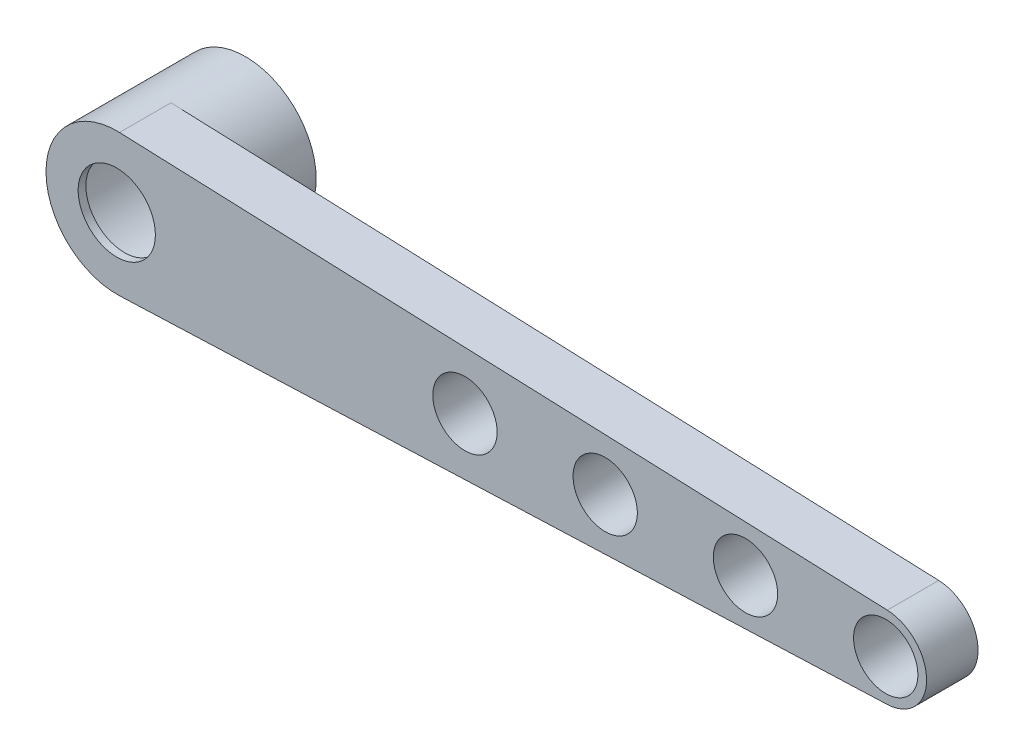
SolidWorks part; units mm, degrees
ref_plane "前视基准面" through (0, 0, 0) normal (0, 0, 1) x (1, 0, 0)
ref_plane "上视基准面" through (0, 0, 0) normal (0, 1, 0) x (1, 0, 0)
ref_plane "右视基准面" through (0, 0, 0) normal (1, 0, 0) x (0, 0, -1)
sketch "草图1" plane through (0, 0, 0) normal (0, 0, 1) x (1, 0, 0)
  circle A0 centre (0, 0) radius 2.75
  dimension "D1" = 5.5
extrude "凸台-拉伸1" add sketch "草图1" along normal blind 5
sketch "草图2" plane through (0, 0, 0) normal (0, 0, -1) x (-1, 0, 0)
  circle A0 centre (0, 0) radius 2.5
  dimension "D1" = 5
extrude "切除-拉伸1" cut sketch "草图2" against normal blind 4.7
sketch "草图3" plane through (0, 0, 5) normal (0, 0, 1) x (1, 0, 0)
  circle A0 centre (0, 0) radius 1.5
  dimension "D1" = 3
extrude "切除-拉伸2" cut sketch "草图3" against normal blind 4.7
sketch "草图4" plane through (0, 0, 5) normal (0, 0, 1) x (1, 0, 0)
  line L0 (0.1066, 2.7479) -> (29.9416, 1.591)
  line L1 (0.1072, -2.7479) -> (29.9419, -1.5841)
  line L2 (16.1859, 13.4331) -> (20.7698, 13.4331)
  line L3 (0.4204, 13.4331) -> (0.4204, 19.2708)
  line L4 (0.4204, 13.4331) -> (16.1859, 13.4331)
  line L5 (0.4204, 19.2708) -> (14.7998, 19.2708)
  line L6 (17.1579, 16.352) -> (1.1299, 16.352) construction
  line L7 (8.3031, 13.4331) -> (8.3031, 19.4331) construction
  line L8 (20.7698, 13.4331) -> (20.7698, 19.2708)
  line L9 (20.7698, 19.2708) -> (14.7998, 19.2708)
  arc A0 (29.9416, 1.591) -> (29.9419, -1.5841) centre (29.88, 0.0035) cw
  circle A2 centre (24.43, 0) radius 1.25
  circle A3 centre (29.88, 0.0035) radius 1.25
  circle A4 centre (0, 0) radius 2.75 construction
  circle A5 centre (2.4204, 16.352) radius 1.25
  circle A6 centre (7.8704, 16.352) radius 1.25
  circle A7 centre (13.3204, 16.352) radius 1.25
  circle A8 centre (18.7698, 16.4323) radius 1.25
  circle A9 centre (18.98, 0) radius 1.25
  circle A10 centre (13.53, 0) radius 1.25
  point P6 (8.1579, 16.4331)
  point P35 (0, 0)
  point P36 (0, 0)
  dimension "D1" = 6
  dimension "D2" = 2.5
  dimension "D3" = 2.5
  dimension "D6" = 2.5
  dimension "D7" = 2.5
  dimension "D8" = 2.5
  dimension "D12" = 2.5
  dimension "D15" = 2.5
  dimension "D16" = 2.5
  dimension "D4" = 29.88
  dimension "D5" = 24.43
  dimension "D9" = 2
  dimension "D10" = 5.45
  dimension "D11" = 5.45
  dimension "D13" = 5.45
  dimension "D14" = 2
  dimension "D17" = 5.45
  dimension "D18" = 5.45
extrude "凸台-拉伸3" add sketch "草图4" against normal blind 2
